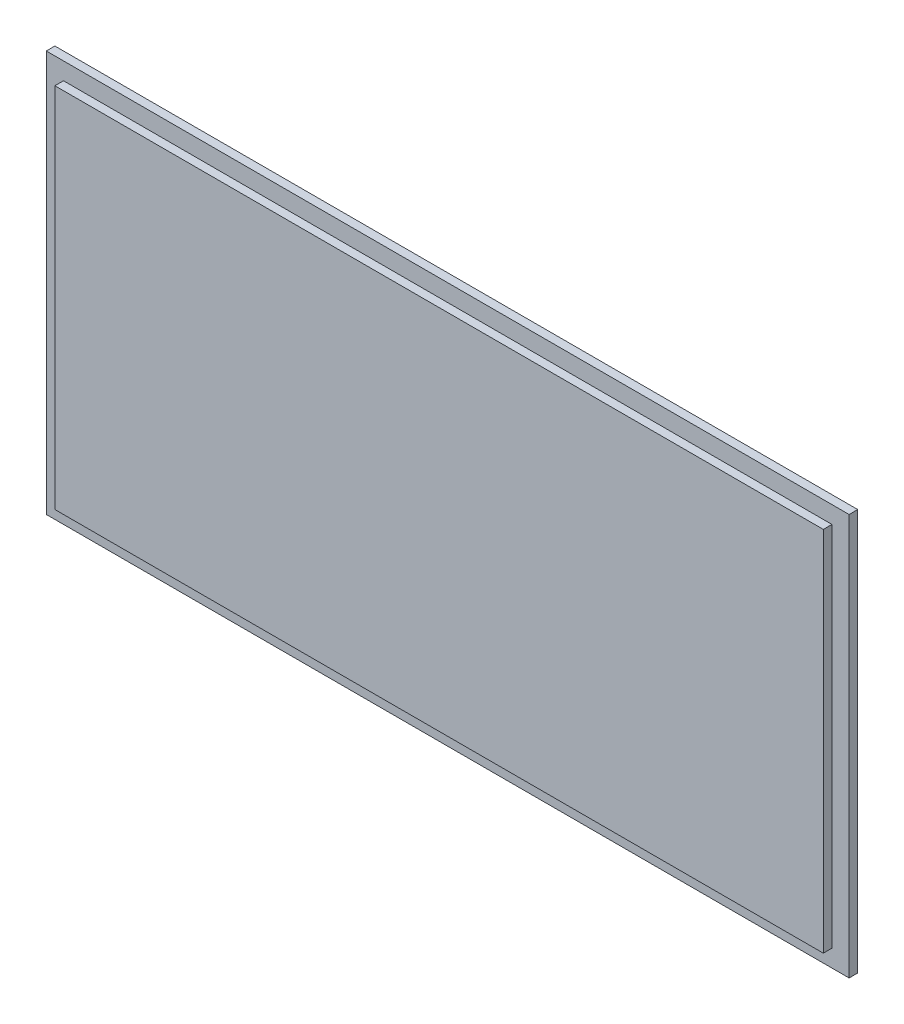
SolidWorks part; units mm, degrees
ref_plane "Спереди" through (0, 0, 0) normal (0, 0, 1) x (1, 0, 0)
ref_plane "Сверху" through (0, 0, 0) normal (0, 1, 0) x (1, 0, 0)
ref_plane "Справа" through (0, 0, 0) normal (1, 0, 0) x (0, 0, -1)
sketch "Эскиз1" plane through (0, 0, 0) normal (0, 0, 1) x (1, 0, 0)
  line L1 (-66.4501, 35.3654) -> (73.5499, 35.3654)
  line L2 (-66.4501, 35.3654) -> (-66.4501, -34.6346)
  line L3 (-66.4501, -34.6346) -> (73.5499, -34.6346)
  line L4 (73.5499, 35.3654) -> (73.5499, -34.6346)
extrude "Бобышка-Вытянуть1" add sketch "Эскиз1" along normal blind 1.5
sketch "Эскиз2" plane through (0, 0, 1.5) normal (0, 0, 1) x (1, 0, 0)
  line L1 (-63.4501, 32.3654) -> (70.5499, 32.3654)
  line L2 (-63.4501, 32.3654) -> (-63.4501, -31.6346)
  line L3 (-63.4501, -31.6346) -> (70.5499, -31.6346)
  line L4 (70.5499, 32.3654) -> (70.5499, -31.6346)
  line L5 (73.5499, 35.3654) -> (-66.4501, 35.3654) construction
  line L6 (-66.4501, 35.3654) -> (-66.4501, -34.6346) construction
  line L7 (-66.4501, -34.6346) -> (73.5499, -34.6346) construction
  line L8 (73.5499, -34.6346) -> (73.5499, 35.3654) construction
  dimension "D1" = 3
  dimension "D2" = 3
  dimension "D3" = 3
  dimension "D4" = 3
extrude "Бобышка-Вытянуть2" add sketch "Эскиз2" along normal blind 1.5 contours L2 L1 L4 L3
